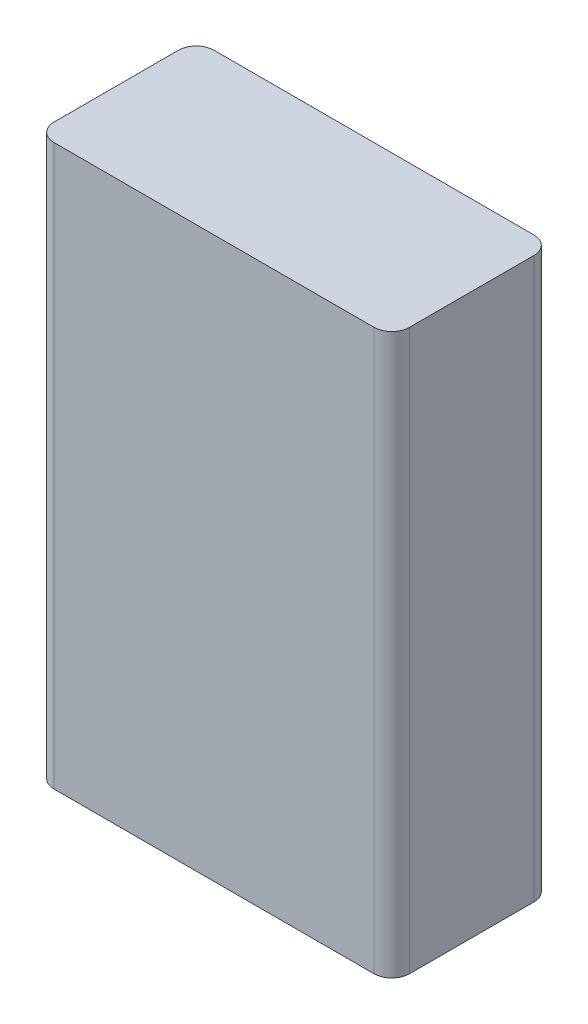
SolidWorks part; units mm, degrees
ref_plane "前视基准面" through (0, 0, 0) normal (0, 0, 1) x (1, 0, 0)
ref_plane "上视基准面" through (0, 0, 0) normal (0, 1, 0) x (1, 0, 0)
ref_plane "右视基准面" through (0, 0, 0) normal (1, 0, 0) x (0, 0, -1)
other "Configuration Table"
sketch "草图1" plane through (0, 0, 0) normal (0, 0, 1) x (1, 0, 0)
  line L0 (0, 0) -> (40, 0)
  line L1 (40, 0) -> (40, 63)
  line L2 (40, 63) -> (0, 63)
  line L3 (0, 63) -> (0, 0)
  dimension "width" = 40
  dimension "height" = 63
extrude "BlockExtrude" add sketch "草图1" along normal blind 18
fillet "Fillet" radius 2 4 edges at (0, 31.5, 0) (40, 31.5, 0) (0, 31.5, 18) (40, 31.5, 18)
